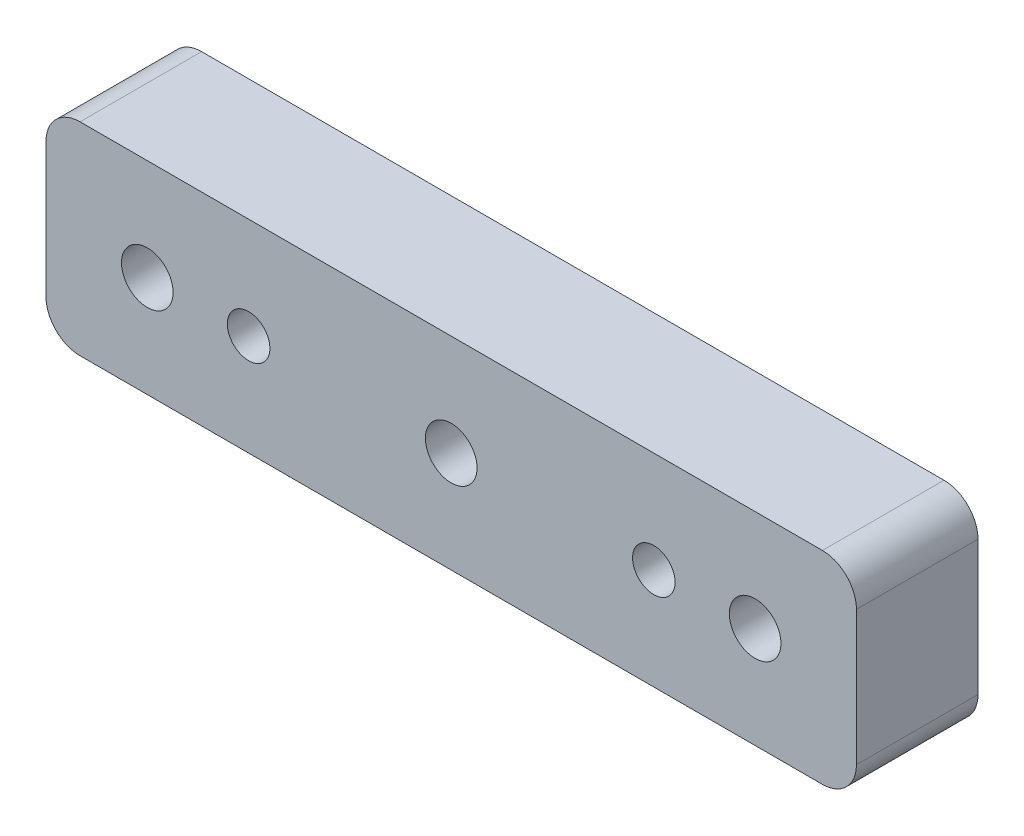
SolidWorks part; units mm, degrees
material "6061-T6 (SS)"
ref_plane "Front Plane" through (0, 0, 0) normal (0, 0, 1) x (1, 0, 0)
ref_plane "Top Plane" through (0, 0, 0) normal (0, 1, 0) x (1, 0, 0)
ref_plane "Right Plane" through (0, 0, 0) normal (1, 0, 0) x (0, 0, -1)
sketch "Sketch1" plane through (0, 0, 0) normal (0, 0, 1) x (1, 0, 0)
  line L1 (36.64, -10) -> (-36.64, -10)
  line L2 (40, -6.64) -> (40, 6.64)
  line L3 (36.64, 10) -> (-36.64, 10)
  line L4 (-40, -6.64) -> (-40, 6.64)
  line L5 (40, -10) -> (-40, 10) construction
  line L6 (40, 10) -> (-40, -10) construction
  arc A0 (40, 6.64) -> (36.64, 10) centre (36.64, 6.64) ccw
  arc A1 (36.64, -10) -> (40, -6.64) centre (36.64, -6.64) ccw
  arc A2 (-36.64, -10) -> (-40, -6.64) centre (-36.64, -6.64) cw
  arc A3 (-36.64, 10) -> (-40, 6.64) centre (-36.64, 6.64) ccw
  point P0 (0, 0)
  dimension "D2" = 3.36
  dimension "D1" = 20
  dimension "D3" = 80
extrude "Boss-Extrude1" add sketch "Sketch1" along normal blind 12
sketch "Sketch3" plane through (0, 0, 12) normal (0, 0, 1) x (1, 0, 0)
  line L0 (0, 0) -> (0, -10) construction
  line L2 (-36.64, -10) -> (36.64, -10) construction
  circle A0 centre (-30, 0) radius 2.55
  circle A1 centre (30, 0) radius 2.55
  circle A2 centre (0, 0) radius 2.55
  dimension "D1" = 5.1
  dimension "D2" = 60
extrude "Cut-Extrude2" cut sketch "Sketch3" against normal through all
hole_wizard "M5x0.8 Tapped Hole1" positions "Sketch5" profile "Sketch4" tap size "M5x0.8" standard "ANSI Metric" end condition through all
sketch "Sketch5" plane through (0, 0, 12) normal (0, 0, 1) x (1, 0, 0)
  line L0 (0, 10) -> (0, 17.067) construction
  line L1 (36.64, 10) -> (-36.64, 10) construction
  point P0 (-20, 0)
  point P10 (20, 0)
  dimension "D1" = 40
sketch "Sketch4" plane through (-20, 0, 12) normal (1, 0, 0) x (0, -1, 0)
  line L0 (0, 0) -> (0, 12)
  line L1 (0, 12) -> (2.1, 12)
  line L2 (2.1, 12) -> (2.1, 0)
  line L5 (2.1, 0) -> (0, 0)
  line L11 (0, -6.35) -> (0, 107.95) construction
  dimension "Thread Major Dia." = 4.2
  dimension "Thru Tap Drill Depth" = 12
